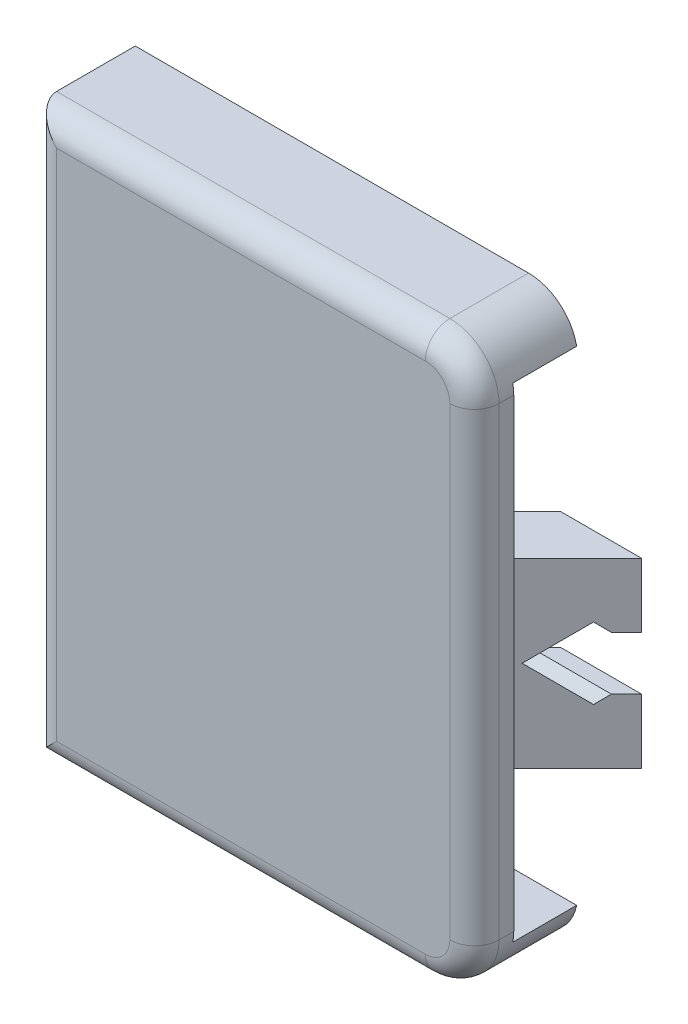
SolidWorks part; units mm, degrees
ref_plane "Front Plane" through (0, 0, 0) normal (0, 0, 1) x (1, 0, 0)
ref_plane "Top Plane" through (0, 0, 0) normal (0, 1, 0) x (1, 0, 0)
ref_plane "Right Plane" through (0, 0, 0) normal (1, 0, 0) x (0, 0, -1)
sketch "Sketch1" plane through (0, 0, 0) normal (0, 0, 1) x (1, 0, 0)
  line L0 (-8.5573, -7.5564) -> (9.4427, -7.5564) construction
  line L1 (-8.5573, 2.2936) -> (9.4427, 2.2936)
  line L2 (-8.5573, 2.2936) -> (-8.5573, -17.4064)
  line L3 (-8.5573, -17.4064) -> (9.4427, -17.4064)
  line L4 (9.4427, 2.2936) -> (9.4427, -17.4064)
  line L5 (-5.2573, -11.2564) -> (-8.5573, -11.2564)
  line L6 (-5.2573, -11.2564) -> (-5.2573, -3.8564)
  line L7 (-8.5573, -11.2564) -> (-8.5573, -3.8564)
  line L8 (-5.2573, -3.8564) -> (-8.5573, -3.8564)
  line L9 (-5.2573, -11.2564) -> (-8.5573, -3.8564) construction
  line L10 (-8.5573, -11.2564) -> (-5.2573, -3.8564) construction
  line L11 (0.4427, 3.8936) -> (0.4427, -17.4064) construction
  line L12 (6.1427, -3.8564) -> (9.4427, -3.8564)
  line L13 (6.1427, -3.8564) -> (6.1427, -11.2564)
  line L14 (6.1427, -11.2564) -> (9.4427, -11.2564)
  line L15 (9.4427, -3.8564) -> (9.4427, -11.2564)
  line L16 (-8.5573, 2.2936) -> (9.4427, 2.2936)
  line L17 (-8.5573, 2.2936) -> (-8.5573, 3.8936)
  line L18 (-8.5573, 3.8936) -> (9.4427, 3.8936)
  line L19 (9.4427, 2.2936) -> (9.4427, 3.8936)
  line L20 (-8.5573, -17.4064) -> (9.4427, -17.4064)
  line L21 (-8.5573, -17.4064) -> (-8.5573, -19.0064)
  line L22 (-8.5573, -19.0064) -> (9.4427, -19.0064)
  line L23 (9.4427, -17.4064) -> (9.4427, -19.0064)
  line L24 (-1.2073, -11.2564) -> (2.0927, -11.2564)
  line L25 (-1.2073, -11.2564) -> (-1.2073, -3.8564)
  line L26 (2.0927, -11.2564) -> (2.0927, -3.8564)
  line L27 (-1.2073, -3.8564) -> (2.0927, -3.8564)
  line L28 (-1.2073, -11.2564) -> (2.0927, -3.8564) construction
  line L29 (2.0927, -11.2564) -> (-1.2073, -3.8564) construction
  line L31 (-8.5573, -3.8564) -> (9.4427, -3.8564)
  line L32 (-8.5573, -3.8564) -> (-8.5573, -11.2564)
  line L33 (-8.5573, -11.2564) -> (9.4427, -11.2564)
  line L34 (9.4427, -3.8564) -> (9.4427, -11.2564)
  point P7 (-6.9073, -7.5564)
  point P22 (0.4427, -7.5564)
  dimension "D1" = 18
  dimension "D2" = 19.7
  dimension "D4" = 7.4
  dimension "D6" = 3.3
  dimension "D7" = 1.6
  dimension "D8" = 1.6
extrude "Boss-Extrude1" add sketch "Sketch1" along normal blind 2.6 contours L27 L25 L24 L26 | L13 L14 L4 L12 | L1 L19 L18 L17 | L23 L3 L21 L22 | L32 L31 L34 L33
sketch "Sketch3" plane through (0, 0, 2.6) normal (0, 0, 1) x (1, 0, 0)
  line L1 (-8.5573, 3.8936) -> (9.4427, 3.8936)
  line L2 (-8.5573, 3.8936) -> (-8.5573, -19.0064)
  line L3 (-8.5573, -19.0064) -> (9.4427, -19.0064)
  line L4 (9.4427, 3.8936) -> (9.4427, -19.0064)
extrude "Boss-Extrude2" add sketch "Sketch3" along normal blind 1.6
sketch "Sketch4" plane through (-8.5573, 0, 0) normal (-1, 0, 0) x (0, 0, 1)
  line L0 (0, -7.5564) -> (4.2, -7.5564) construction
  line L1 (0, -3.8564) -> (0, -11.2564) construction
  line L2 (4.2, 3.8936) -> (4.2, -19.0064) construction
  line L3 (-0.4745, -7.5564) -> (0.9779, -6.104)
  line L4 (-0.4745, -7.5564) -> (0.9779, -9.0088)
  line L5 (0.9779, -6.104) -> (2.4303, -7.5564)
  line L6 (0.9779, -9.0088) -> (2.4303, -7.5564)
  line L7 (-0.4745, -7.5564) -> (2.4303, -7.5564) construction
  line L8 (0.9779, -6.104) -> (0.9779, -9.0088) construction
  line L10 (-0.631, -6.4685) -> (1.3424, -6.4685)
  line L11 (-0.631, -6.4685) -> (-0.631, -8.6443)
  line L12 (-0.631, -8.6443) -> (1.3424, -8.6443)
  line L13 (1.3424, -6.4685) -> (1.3424, -8.6443)
  line L14 (-0.631, -6.4685) -> (1.3424, -8.6443) construction
  line L15 (-0.631, -8.6443) -> (1.3424, -6.4685) construction
  point P7 (0.9779, -7.5564)
  point P9 (0.3557, -7.5564)
extrude "Cut-Extrude1" cut sketch "Sketch4" against normal through all both and the other way through all
fillet "Fillet1" radius 2 2 edges at (9.4427, 3.8936, 2.1) (9.4427, -19.0064, 2.1)
fillet "Fillet2" radius 1 6 edges at (8.8569, 3.3078, 4.2) (9.4427, -7.5564, 4.2) (8.8569, -18.4206, 4.2) (-0.5573, -19.0064, 4.2) (-8.5573, -7.5564, 4.2) (-0.5573, 3.8936, 4.2)
sketch "Sketch6" plane through (9.4427, 0, 0) normal (1, 0, 0) x (0, 0, -1)
  line L0 (-2.6, -3.8564) -> (-2.6, -11.2564)
  line L1 (-2.6, -11.2564) -> (0, -11.2564)
  line L2 (0, -11.2564) -> (0, -8.6443)
  line L3 (0, -8.6443) -> (-0.6134, -8.6443)
  line L4 (-0.6134, -8.6443) -> (-0.9779, -9.0088)
  line L5 (-0.9779, -9.0088) -> (-2.4303, -7.5564)
  line L6 (-2.4303, -7.5564) -> (-0.9779, -6.104)
  line L7 (-0.9779, -6.104) -> (-0.6134, -6.4685)
  line L8 (-0.6134, -6.4685) -> (0, -6.4685)
  line L9 (0, -6.4685) -> (0, -3.8564)
  line L10 (0, -3.8564) -> (-2.6, -3.8564)
extrude "Boss-Extrude3" add sketch "Sketch6" along normal blind 5
sketch "Sketch5" plane through (0, -11.2564, 0) normal (0, -1, 0) x (1, 0, 0)
  line L0 (-5.2573, 2.6) -> (-1.2073, 2.6)
  line L1 (-5.2573, 2.6) -> (-2.2406, -0.4167)
  line L2 (-1.2073, 2.6) -> (1.8094, -0.4167)
  line L3 (-2.2406, -0.4167) -> (1.8094, -0.4167)
  line L4 (2.0927, 2.6) -> (6.1427, 2.6)
  line L5 (2.0927, 2.6) -> (6.3967, -1.704)
  line L6 (6.1427, 2.6) -> (10.4467, -1.704)
  line L7 (6.3967, -1.704) -> (10.4467, -1.704)
  line L8 (-8.5573, 2.6) -> (-13.2005, 2.6)
  line L9 (-8.5573, 2.6) -> (-5.4785, -0.4788)
  line L10 (-13.2005, 2.6) -> (-10.1218, -0.4788)
  line L11 (-5.4785, -0.4788) -> (-10.1218, -0.4788)
  line L12 (9.4427, 2.6) -> (15.4565, 2.6)
  line L13 (9.4427, 2.6) -> (13.4538, -1.4111)
  line L14 (15.4565, 2.6) -> (19.4676, -1.4111)
  line L15 (13.4538, -1.4111) -> (19.4676, -1.4111)
  point P19 (-5.2573, 2.6)
  point P20 (-1.2073, 2.6)
  point P21 (2.0927, 2.6)
  point P22 (6.1427, 2.6)
  point P23 (9.4427, 2.6)
extrude "Cut-Extrude2" cut sketch "Sketch5" against normal blind 10
